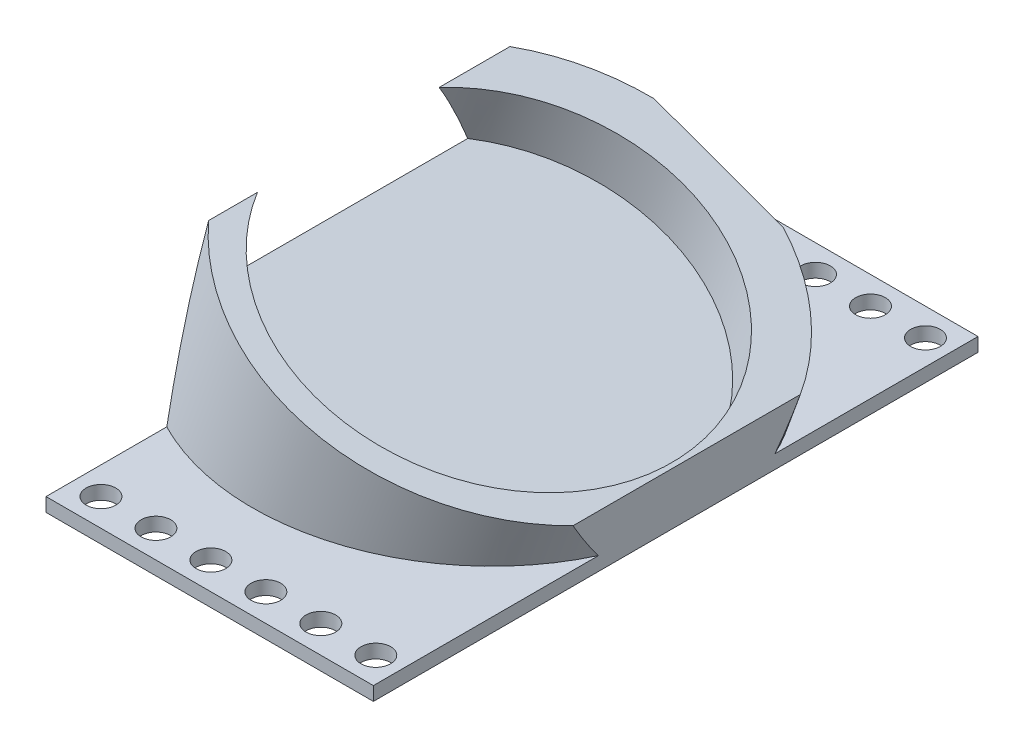
SolidWorks part; units mm, degrees
ref_plane "Front Plane" through (0, 0, 0) normal (0, 0, 1) x (1, 0, 0)
ref_plane "Top Plane" through (0, 0, 0) normal (0, 1, 0) x (1, 0, 0)
ref_plane "Right Plane" through (0, 0, 0) normal (1, 0, 0) x (0, 0, -1)
sketch "Sketch1" plane through (0, 0, 0) normal (0, 0, 1) x (1, 0, 0)
  line L1 (-139.7, -127) -> (88.9, -127)
  line L2 (-139.7, -127) -> (-139.7, 0)
  line L3 (-139.7, 0) -> (88.9, 0)
  line L4 (88.9, -127) -> (88.9, 0)
  line L5 (-139.7, -127) -> (88.9, 0) construction
  line L6 (-139.7, 0) -> (88.9, -127) construction
  point P0 (0, 0)
  dimension "D1" = 228.6
  dimension "D2" = 127
  dimension "D3" = 88.9
extrude "Boss-Extrude1" add sketch "Sketch1" along normal mid plane 101.6
sketch "Sketch2" plane through (0, 0, 0) normal (0, 0, 1) x (1, 0, 0)
  line L0 (-60.424, -168.5535) -> (0, -2.54) construction
  line L1 (-50.5032, -16.9031) -> (-105.9967, 3.2949)
  line L2 (-14.8676, -43.3884) -> (-54.8468, -28.8372)
  line L3 (-54.8468, -28.8372) -> (-50.5032, -16.9031)
  line L4 (-105.9967, 3.2949) -> (-55.1834, 142.9033)
  line L5 (-10.524, -31.4543) -> (-50.5032, -16.9031) construction
  line L7 (0, -2.54) -> (40.2893, 108.1541)
  line L8 (-83.8, -2.54) -> (0, -2.54) construction
  line L9 (-55.1834, 142.9033) -> (40.2893, 108.1541)
  line L10 (0, -2.54) -> (-14.8676, -43.3884)
  line L11 (88.9, 0) -> (-139.7, 0) construction
  point P2 (0, 0)
  point P3 (0, 0)
  point P11 (-46.7329, -130.9377)
  point P12 (0, 0)
  point P15 (0, 0)
  point P17 (-13.8063, -40.4726)
  point P23 (-10.524, -31.4543)
  dimension "D1" = 70
  dimension "D2" = 12.7
  dimension "D3" = 2.54
  dimension "D4" = 30.77
  dimension "D5" = 42.545
  dimension "D6" = 101.6
revolve "Cut-Revolve1" cut sketch "Sketch2" angle 360 about L0
sketch "Sketch30" plane through (0, 0, 0) normal (0, 0, 1) x (1, 0, 0)
  line L0 (-139.7, -127) -> (88.9, -127) construction
  line L1 (-139.7, 0) -> (-45.2997, 0)
  line L2 (-139.7, 0) -> (-139.7, -127)
  line L3 (-139.7, -127) -> (-45.2997, -127)
  line L4 (-45.2997, 0) -> (-45.2997, -127)
  line L5 (0, -2.54) -> (-14.8676, -43.3884) construction
  line L6 (88.9, 0) -> (30.3406, 0)
  line L7 (88.9, 0) -> (88.9, -127)
  line L8 (88.9, -127) -> (30.3406, -127)
  line L9 (30.3406, 0) -> (30.3406, -127)
  point P12 (-45.2997, -127)
  point P15 (-45.2997, -127)
  point P16 (-45.2997, -127)
extrude "Cut-Extrude24" cut sketch "Sketch30" against normal through all both and the other way through all
sketch "Sketch31" plane through (0, -127, 0) normal (0, -1, 0) x (1, 0, 0)
  line L5 (30.3406, 50.8) -> (-45.2997, 50.8)
  line L6 (-45.2997, 50.8) -> (-45.2997, -50.8)
  line L8 (-45.2997, -50.8) -> (30.3406, -50.8)
  line L9 (30.3406, -50.8) -> (30.3406, 50.8)
  line L10 (30.3406, 50.8) -> (-45.2997, 50.8)
  line L11 (-45.2997, 50.8) -> (-45.2997, -50.8)
  line L13 (-45.2997, -50.8) -> (30.3406, -50.8)
  line L14 (30.3406, -50.8) -> (30.3406, 50.8)
  dimension "D1" = 0
extrude "Cut-Extrude25" cut sketch "Sketch31" against normal blind 68.58
sketch "Sketch32" plane through (-15.684, -43.0913, 0) normal (0.342, 0.9397, 0) x (0.9397, -0.342, 0)
  circle A0 centre (0.8687, 2.54) radius 50.8
  circle A1 centre (0.8687, 0) radius 2.54 construction
  dimension "D1" = 101.6
extrude "Cut-Extrude26" cut sketch "Sketch32" against normal through all both and the other way through all flip side to cut
sketch "Sketch34" plane through (0, -58.42, 0) normal (0, -1, 0) x (1, 0, 0)
  line L0 (-45.2997, 27.5912) -> (-45.2997, -27.5912) construction
  line L1 (45.2997, -69.85) -> (-45.2997, -69.85)
  line L2 (45.2997, -69.85) -> (45.2997, 69.85)
  line L3 (45.2997, 69.85) -> (-45.2997, 69.85)
  line L4 (-45.2997, -69.85) -> (-45.2997, 69.85)
  line L5 (45.2997, -69.85) -> (-45.2997, 69.85) construction
  line L6 (45.2997, 69.85) -> (-45.2997, -69.85) construction
  line L7 (0, 0) -> (40.2893, 0) construction
  line L8 (8.1833, 23.6312) -> (17.5705, 30.3681)
  line L9 (17.5705, 30.3681) -> (24.5503, 23.6312)
  line L10 (24.5503, 23.6312) -> (27.6117, 8.5779)
  line L11 (27.6117, 8.5779) -> (26.081, -20.9116)
  line L12 (26.081, -20.9116) -> (15.4101, -35.9889)
  line L13 (15.4101, -35.9889) -> (9.9999, -28.4503)
  line L14 (9.9999, -28.4503) -> (8.1833, 23.6312)
  circle A0 centre (-38.9497, 63.5) radius 3.429
  circle A1 centre (-26.2497, 63.5) radius 3.429
  circle A2 centre (-13.5497, 63.5) radius 3.429
  circle A3 centre (-0.8497, 63.5) radius 3.429
  circle A4 centre (11.8503, 63.5) radius 3.429
  circle A5 centre (24.5503, 63.5) radius 3.429
  circle A6 centre (-26.2497, -63.5) radius 3.429
  circle A7 centre (-13.5497, -63.5) radius 3.429
  circle A8 centre (-0.8497, -63.5) radius 3.429
  circle A9 centre (11.8503, -63.5) radius 3.429
  circle A10 centre (24.5503, -63.5) radius 3.429
  circle A11 centre (-38.9497, -63.5) radius 3.429
  point P0 (0, 0)
  dimension "D1" = 6.858
  dimension "D2" = 69.85
  dimension "D3" = 6.35
  dimension "D4" = 63.5
  dimension "D5" = 6
  dimension "D6" = 2
extrude "Boss-Extrude2" add sketch "Sketch34" against normal blind 3.175
sketch "Sketch35" plane through (0, -55.245, 0) normal (0, 1, 0) x (1, 0, 0)
  line L0 (30.3406, 28.7985) -> (30.3406, 69.85)
  line L1 (-45.2997, 69.85) -> (45.2997, 69.85) construction
  line L2 (30.3406, 69.85) -> (45.2997, 69.85)
  line L3 (45.2997, 69.85) -> (45.2997, -69.85)
  line L4 (45.2997, -69.85) -> (30.3406, -69.85)
  line L5 (45.2997, -69.85) -> (-45.2997, -69.85) construction
  line L6 (30.3406, -69.85) -> (30.3406, 28.7985)
extrude "Cut-Extrude28" cut sketch "Sketch35" along normal through all both and the other way through all
